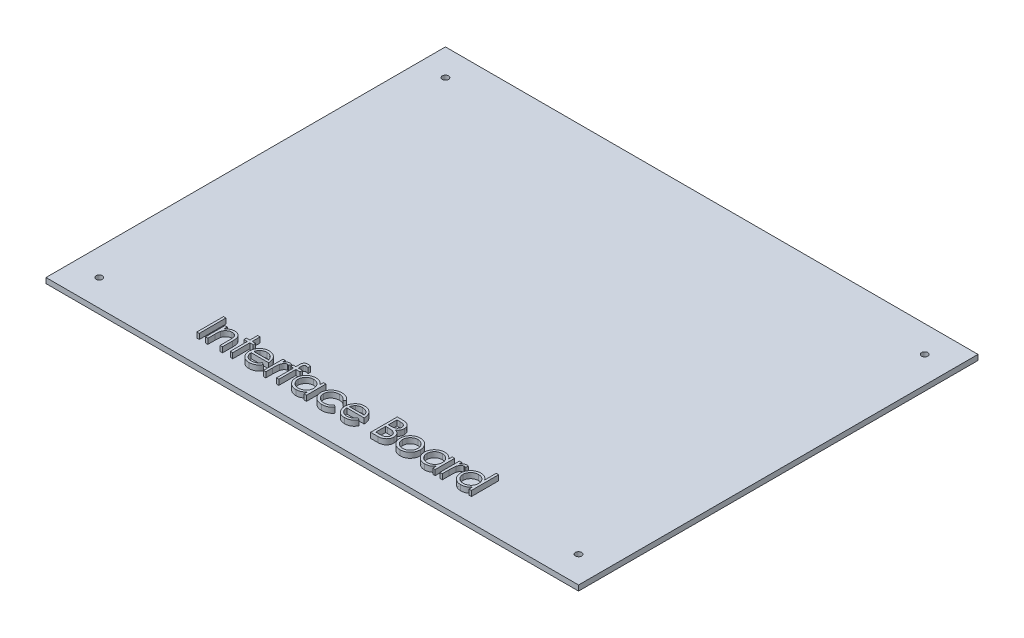
SolidWorks part; units mm, degrees
ref_plane "Front Plane" through (0, 0, 0) normal (0, 0, 1) x (1, 0, 0)
ref_plane "Top Plane" through (0, 0, 0) normal (0, 1, 0) x (1, 0, 0)
ref_plane "Right Plane" through (0, 0, 0) normal (1, 0, 0) x (0, 0, -1)
sketch "Sketch1" plane through (0, 0, 0) normal (0, 1, 0) x (1, 0, 0)
  line L1 (127, -95.25) -> (-127, -95.25)
  line L2 (127, -95.25) -> (127, 95.25)
  line L3 (127, 95.25) -> (-127, 95.25)
  line L4 (-127, -95.25) -> (-127, 95.25)
  line L5 (127, -95.25) -> (-127, 95.25) construction
  line L6 (127, 95.25) -> (-127, -95.25) construction
  point P0 (0, 0)
  dimension "D1" = 190.5
  dimension "D2" = 254
extrude "Boss-Extrude1" add sketch "Sketch1" along normal blind 2.54
hole_wizard "Ø3.0mm Dowel Hole1" positions "Sketch3" profile "Sketch4" hole size "Ø3.0" standard "AS" end condition through all
sketch "Sketch3" plane through (0, 2.54, 0) normal (0, 1, 0) x (1, 0, 0)
  line L0 (-127, 95.25) -> (-127, -95.25) construction
  line L1 (127, 95.25) -> (-127, 95.25) construction
  line L2 (127, -95.25) -> (127, 95.25) construction
  line L3 (-127, -95.25) -> (127, -95.25) construction
  point P0 (-114.3, 82.55)
  point P2 (114.3, 82.55)
  point P4 (114.3, -82.55)
  point P6 (-114.3, -82.55)
  dimension "D1" = 12.7
  dimension "D2" = 12.7
  dimension "D3" = 12.7
  dimension "D4" = 12.7
  dimension "D5" = 12.7
  dimension "D6" = 12.7
  dimension "D7" = 12.7
  dimension "D8" = 12.7
sketch "Sketch4" plane through (-114.3, 2.54, -82.55) normal (1, 0, 0) x (0, 0, 1)
  line L0 (0, 0) -> (0, 2.54)
  line L1 (0, 2.54) -> (1.5, 2.54)
  line L2 (1.5, 2.54) -> (1.5, 0)
  line L5 (1.5, 0) -> (0, 0)
  line L11 (0, -6.35) -> (0, 107.95) construction
  dimension "Thru Hole Dia." = 3
  dimension "Thru Hole Depth" = 2.54
sketch "Sketch5" plane through (0, 2.54, 0) normal (0, 1, 0) x (1, 0, 0)
  text T0 "Interface Board" font "Century Gothic" height in points 48
extrude "Boss-Extrude2" add sketch "Sketch5" along normal blind 2.54
